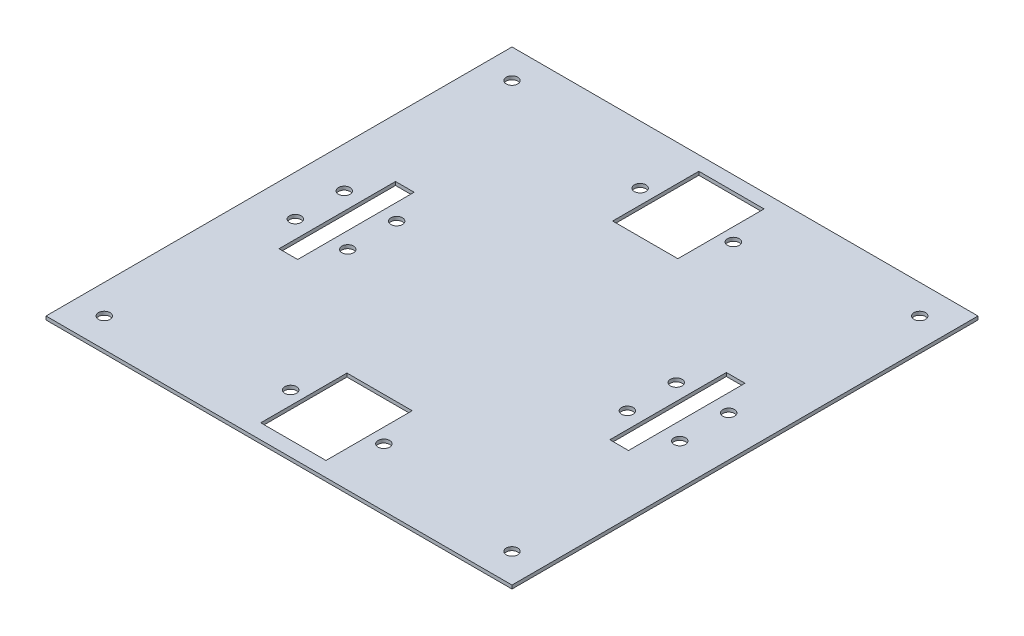
SolidWorks part; units mm, degrees
ref_plane "Front Plane" through (0, 0, 0) normal (0, 0, 1) x (1, 0, 0)
ref_plane "Top Plane" through (0, 0, 0) normal (0, 1, 0) x (1, 0, 0)
ref_plane "Right Plane" through (0, 0, 0) normal (1, 0, 0) x (0, 0, -1)
sketch "Sketch1" plane through (0, 0, 0) normal (0, 1, 0) x (1, 0, 0)
  line L1 (-200, 200) -> (200, 200)
  line L2 (-200, 200) -> (-200, -200)
  line L3 (-200, -200) -> (200, -200)
  line L4 (200, 200) -> (200, -200)
  line L5 (-200, 200) -> (200, -200) construction
  line L6 (-200, -200) -> (200, 200) construction
  point P0 (0, 0)
  dimension "D1" = 400
  dimension "D2" = 400
extrude "Boss-Extrude1" add sketch "Sketch1" along normal blind 3
sketch "Sketch3" plane through (0, 3, 0) normal (0, 1, 0) x (1, 0, 0)
  line L1 (-149.9907, 50.0058) -> (-133.9907, 50.0058)
  line L2 (-149.9907, 50.0058) -> (-149.9907, -49.9942)
  line L3 (-149.9907, -49.9942) -> (-133.9907, -49.9942)
  line L4 (-133.9907, 50.0058) -> (-133.9907, -49.9942)
  line L5 (-149.9907, 50.0058) -> (-133.9907, -49.9942) construction
  line L6 (-149.9907, -49.9942) -> (-133.9907, 50.0058) construction
  line L7 (133.9965, 50.0057) -> (149.9965, 50.0057)
  line L8 (133.9965, 50.0057) -> (133.9965, -49.9943)
  line L9 (133.9965, -49.9943) -> (149.9965, -49.9943)
  line L10 (149.9965, 50.0057) -> (149.9965, -49.9943)
  line L11 (133.9965, 50.0057) -> (149.9965, -49.9943) construction
  line L12 (133.9965, -49.9943) -> (149.9965, 50.0057) construction
  point P0 (-141.9907, 0.0058)
  point P5 (141.9965, 0.0057)
extrude "Cut-Extrude1" cut sketch "Sketch3" against normal blind 3
sketch "Sketch4" plane through (0, 3, 0) normal (0, 1, 0) x (1, 0, 0)
  line L1 (-27.3921, 187.77) -> (28.6079, 187.77)
  line L2 (-27.3921, 187.77) -> (-27.3921, 113.77)
  line L3 (-27.3921, 113.77) -> (28.6079, 113.77)
  line L4 (28.6079, 187.77) -> (28.6079, 113.77)
  line L5 (-27.3921, 187.77) -> (28.6079, 113.77) construction
  line L6 (-27.3921, 113.77) -> (28.6079, 187.77) construction
  line L7 (-28.4349, -113.2412) -> (27.5651, -113.2412)
  line L8 (-28.4349, -113.2412) -> (-28.4349, -187.2412)
  line L9 (-28.4349, -187.2412) -> (27.5651, -187.2412)
  line L10 (27.5651, -113.2412) -> (27.5651, -187.2412)
  line L11 (-28.4349, -113.2412) -> (27.5651, -187.2412) construction
  line L12 (-28.4349, -187.2412) -> (27.5651, -113.2412) construction
  point P0 (0.6079, 150.77)
  point P5 (-0.4349, -150.2412)
extrude "Cut-Extrude2" cut sketch "Sketch4" against normal blind 3
sketch "Sketch5" plane through (0, 3, 0) normal (0, 1, 0) x (1, 0, 0)
  line L0 (-40, 150) -> (40, 150) construction
  line L1 (-165, 21) -> (-165, -21) construction
  line L2 (-165, -21) -> (-120, -21) construction
  line L3 (120, 21) -> (120, -21) construction
  line L4 (120, -21) -> (165, -21) construction
  circle A0 centre (-165, 21) radius 5
  circle A1 centre (-165, -21) radius 5
  circle A2 centre (-120, 21) radius 5
  circle A3 centre (-120, -21) radius 5
  circle A4 centre (165, 21) radius 5
  circle A5 centre (165, -21) radius 5
  circle A6 centre (120, 21) radius 5
  circle A7 centre (120, -21) radius 5
  circle A8 centre (-40, -150) radius 5
  circle A9 centre (40, -150) radius 5
  circle A10 centre (-40, 150) radius 5
  circle A11 centre (40, 150) radius 5
  circle A12 centre (-175, 175) radius 5
  circle A13 centre (175, 175) radius 5
  circle A14 centre (175, -175) radius 5
  circle A15 centre (-175, -175) radius 5
extrude "Cut-Extrude3" cut sketch "Sketch5" against normal blind 3
